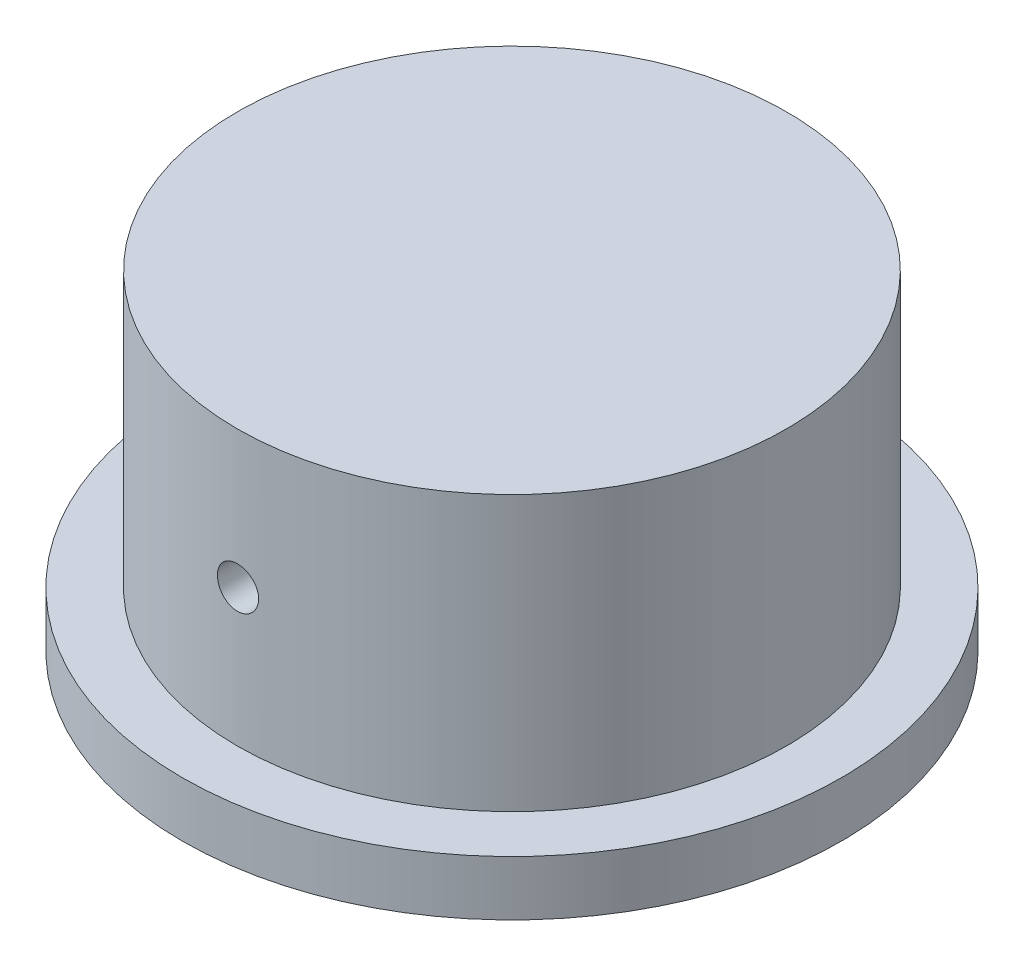
SolidWorks part; units mm, degrees
ref_plane "前视基准面" through (0, 0, 0) normal (0, 0, 1) x (1, 0, 0)
ref_plane "上视基准面" through (0, 0, 0) normal (0, 1, 0) x (1, 0, 0)
ref_plane "右视基准面" through (0, 0, 0) normal (1, 0, 0) x (0, 0, -1)
other "Configuration Table"
sketch "草图1" plane through (0, 0, 0) normal (0, 1, 0) x (1, 0, 0)
  circle A0 centre (0, 0) radius 12
extrude "凸台-拉伸1" add sketch "草图1" along normal blind 2
sketch "草图2" plane through (0, 2, 0) normal (0, 1, 0) x (1, 0, 0)
  circle A0 centre (0, 0) radius 10
extrude "凸台-拉伸2" add sketch "草图2" along normal blind 10
sketch "草图3" plane through (0, 0, 0) normal (0, 0, 1) x (1, 0, 0)
  circle A0 centre (0, 7) radius 0.75
extrude "切除-拉伸1" cut sketch "草图3" against normal mid plane 60
